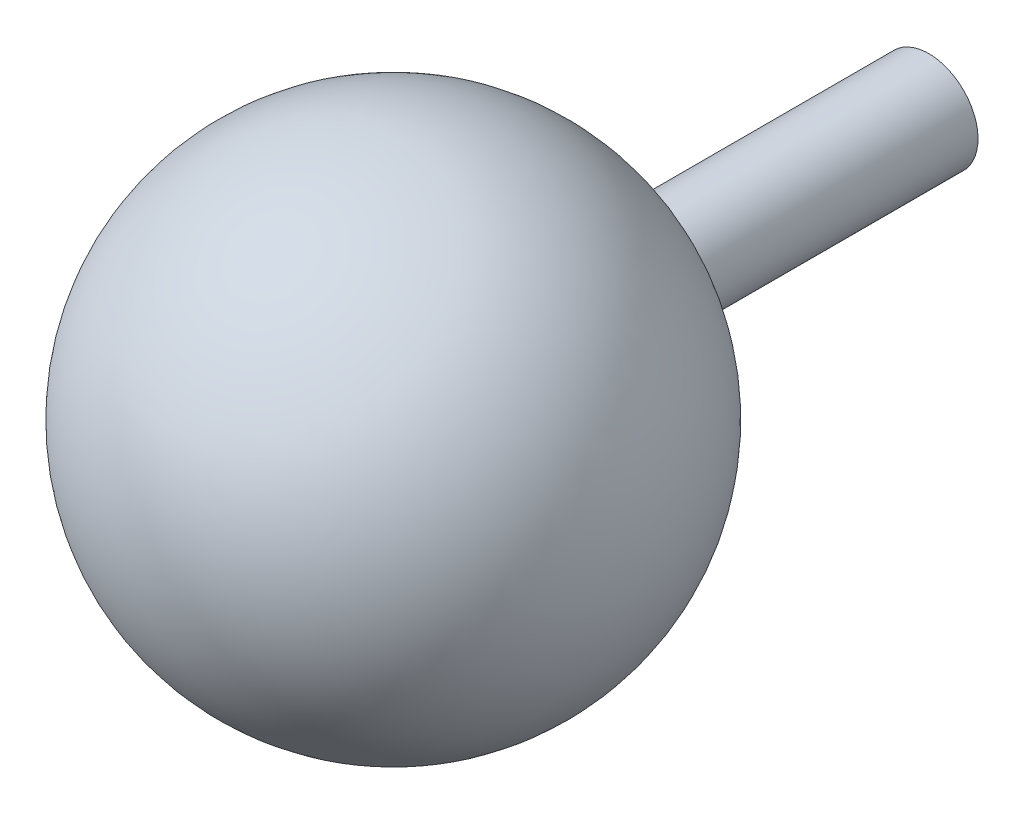
SolidWorks part; units mm, degrees
ref_plane "前视基准面" through (0, 0, 0) normal (0, 0, 1) x (1, 0, 0)
ref_plane "上视基准面" through (0, 0, 0) normal (0, 1, 0) x (1, 0, 0)
ref_plane "右视基准面" through (0, 0, 0) normal (1, 0, 0) x (0, 0, -1)
other "Configuration Table"
sketch "草图1" plane through (0, 0, 0) normal (0, 0, 1) x (1, 0, 0)
  line L0 (0, 5) -> (0, -5)
  arc A0 (0, -5) -> (0, 5) centre (0, 0) ccw
  arc A1 (0, -4.9) -> (0, 4.9) centre (0, 0) ccw
  dimension "D1" = 10
  dimension "D2" = 9.8
revolve "旋转2" add sketch "草图1" angle 360 about L0
sketch "草图2" plane through (0, 0, 0) normal (0, 1, 0) x (1, 0, 0)
  circle A0 centre (0, 0) radius 2.2735
extrude "切除-拉伸1" cut sketch "草图2" against normal blind 10
sketch "草图3" plane through (0, 0, 0) normal (1, 0, 0) x (0, 0, -1)
  line L0 (-0.899, 0) -> (10.899, 0)
  line L1 (4.899, -1) -> (10.899, -1)
  line L2 (4.899, -1) -> (4.899, 1)
  line L3 (4.899, 1) -> (10.899, 1)
  line L4 (10.899, -1) -> (10.899, 1)
  line L5 (4.899, -1) -> (10.899, 1) construction
  line L6 (4.899, 1) -> (10.899, -1) construction
  arc A0 (2.2735, -4.4532) -> (-2.2735, -4.4532) centre (0, 0) ccw construction
  point P0 (5, 0)
  point P10 (4.8888, -1.0386)
  point P11 (4.9099, 0.9451)
  dimension "D1" = 6
  dimension "D2" = 2
revolve "旋转4" add sketch "草图3" angle 360 about L0
sketch "草图4" plane through (0, 0, 0) normal (1, 0, 0) x (0, 0, -1)
  line L0 (-2.2735, -4.4532) -> (2.2735, -4.4532) construction
  line L1 (0, -4.0205) -> (0, -4.8859) construction
  circle A0 centre (0, -4.4532) radius 0.4327
revolve "旋转6" add sketch "草图4" angle 360 about L1
